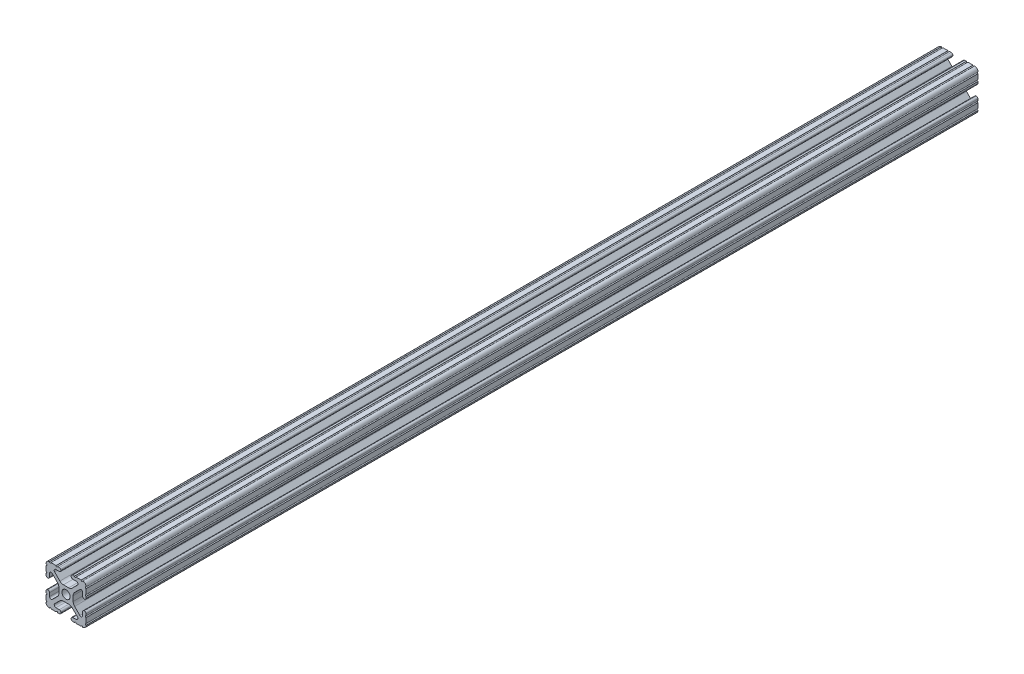
SolidWorks part; units mm, degrees
ref_plane "Front Plane" through (0, 0, 0) normal (0, 0, 1) x (1, 0, 0)
ref_plane "Top Plane" through (0, 0, 0) normal (0, 1, 0) x (1, 0, 0)
ref_plane "Right Plane" through (0, 0, 0) normal (1, 0, 0) x (0, 0, -1)
sketch "Sketch1" plane through (0, 0, 0) normal (0, 0, 1) x (1, 0, 0)
  line L88 (-7.1797, -8.6452) -> (-3.9523, -5.4237)
  line L89 (-1.7093, -4.4958) -> (1.7093, -4.4958)
  line L90 (3.9523, -5.4237) -> (7.1797, -8.6452)
  line L91 (6.4164, -10.4902) -> (4.2875, -10.4902)
  line L92 (3.2385, -11.5392) -> (3.2385, -11.651)
  line L93 (4.2875, -12.7) -> (5.3171, -12.7)
  line L94 (6.3331, -12.7) -> (9.5504, -12.7)
  line L95 (12.7, -9.5504) -> (12.7, -6.3331)
  line L96 (12.7, -5.3171) -> (12.7, -4.2875)
  line L97 (11.651, -3.2385) -> (11.5392, -3.2385)
  line L98 (10.4902, -4.2875) -> (10.4902, -6.4021)
  line L99 (8.7371, -7.1294) -> (5.441, -3.8408)
  line L100 (4.5085, -1.5932) -> (4.5085, 1.5932)
  line L101 (5.441, 3.8408) -> (8.7371, 7.1294)
  line L102 (10.4902, 6.4021) -> (10.4902, 4.2875)
  line L103 (11.5392, 3.2385) -> (11.651, 3.2385)
  line L104 (12.7, 4.2875) -> (12.7, 5.3171)
  line L105 (12.7, 6.3331) -> (12.7, 9.5504)
  line L106 (9.5504, 12.7) -> (6.3331, 12.7)
  line L107 (5.3171, 12.7) -> (4.2875, 12.7)
  line L108 (3.2385, 11.651) -> (3.2385, 11.5392)
  line L109 (4.2875, 10.4902) -> (6.4768, 10.4902)
  line L110 (7.207, 8.7244) -> (3.8983, 5.4232)
  line L111 (1.6558, 4.4958) -> (-1.6558, 4.4958)
  line L112 (-3.8983, 5.4232) -> (-7.207, 8.7244)
  line L113 (-6.4768, 10.4902) -> (-4.2875, 10.4902)
  line L114 (-3.2385, 11.5392) -> (-3.2385, 11.651)
  line L115 (-4.2875, 12.7) -> (-5.3171, 12.7)
  line L116 (-6.3331, 12.7) -> (-9.5504, 12.7)
  line L117 (-12.7, 9.5504) -> (-12.7, 6.3331)
  line L118 (-12.7, 5.3171) -> (-12.7, 4.2875)
  line L119 (-11.651, 3.2385) -> (-11.5392, 3.2385)
  line L120 (-10.4902, 4.2875) -> (-10.4902, 6.4021)
  line L121 (-8.7371, 7.1294) -> (-5.441, 3.8408)
  line L122 (-4.5085, 1.5932) -> (-4.5085, -1.5932)
  line L123 (-5.441, -3.8408) -> (-8.7371, -7.1294)
  line L124 (-10.4902, -6.4021) -> (-10.4902, -4.2875)
  line L125 (-11.5392, -3.2385) -> (-11.651, -3.2385)
  line L126 (-12.7, -4.2875) -> (-12.7, -5.3171)
  line L127 (-12.7, -6.3331) -> (-12.7, -9.5504)
  line L128 (-9.5504, -12.7) -> (-6.3331, -12.7)
  line L129 (-5.3171, -12.7) -> (-4.2875, -12.7)
  line L130 (-3.2385, -11.651) -> (-3.2385, -11.5392)
  line L131 (-4.2875, -10.4902) -> (-6.4164, -10.4902)
  circle A1 centre (0, 0) radius 2.6035
  arc A104 (-7.1797, -8.6452) -> (-6.4164, -10.4902) centre (-6.4164, -9.4098) ccw
  arc A105 (-1.7093, -4.4958) -> (-3.9523, -5.4237) centre (-1.7093, -7.6708) ccw
  arc A106 (3.9523, -5.4237) -> (1.7093, -4.4958) centre (1.7093, -7.6708) ccw
  arc A107 (6.4164, -10.4902) -> (7.1797, -8.6452) centre (6.4164, -9.4098) ccw
  arc A108 (4.2875, -10.4902) -> (3.2385, -11.5392) centre (4.2875, -11.5392) ccw
  arc A109 (3.2385, -11.651) -> (4.2875, -12.7) centre (4.2875, -11.651) ccw
  arc A110 (6.3331, -12.7) -> (5.3171, -12.7) centre (5.8251, -12.7) ccw
  arc A111 (10.5664, -12.6998) -> (9.5504, -12.7) centre (10.0584, -12.7) ccw
  arc A112 (10.5664, -12.6998) -> (12.6998, -10.5664) centre (10.5918, -10.5918) ccw
  arc A113 (12.7, -9.5504) -> (12.6998, -10.5664) centre (12.7, -10.0584) ccw
  arc A114 (12.7, -5.3171) -> (12.7, -6.3331) centre (12.7, -5.8251) ccw
  arc A115 (12.7, -4.2875) -> (11.651, -3.2385) centre (11.651, -4.2875) ccw
  arc A116 (11.5392, -3.2385) -> (10.4902, -4.2875) centre (11.5392, -4.2875) ccw
  arc A117 (8.7371, -7.1294) -> (10.4902, -6.4021) centre (9.4628, -6.4021) ccw
  arc A118 (4.5085, -1.5932) -> (5.441, -3.8408) centre (7.6835, -1.5932) ccw
  arc A119 (5.441, 3.8408) -> (4.5085, 1.5932) centre (7.6835, 1.5932) ccw
  arc A120 (10.4902, 6.4021) -> (8.7371, 7.1294) centre (9.4628, 6.4021) ccw
  arc A121 (10.4902, 4.2875) -> (11.5392, 3.2385) centre (11.5392, 4.2875) ccw
  arc A122 (11.651, 3.2385) -> (12.7, 4.2875) centre (11.651, 4.2875) ccw
  arc A123 (12.7, 6.3331) -> (12.7, 5.3171) centre (12.7, 5.8251) ccw
  arc A124 (12.6998, 10.5664) -> (12.7, 9.5504) centre (12.7, 10.0584) ccw
  arc A125 (12.6998, 10.5664) -> (10.5664, 12.6998) centre (10.5918, 10.5918) ccw
  arc A126 (9.5504, 12.7) -> (10.5664, 12.6998) centre (10.0584, 12.7) ccw
  arc A127 (5.3171, 12.7) -> (6.3331, 12.7) centre (5.8251, 12.7) ccw
  arc A128 (4.2875, 12.7) -> (3.2385, 11.651) centre (4.2875, 11.651) ccw
  arc A129 (3.2385, 11.5392) -> (4.2875, 10.4902) centre (4.2875, 11.5392) ccw
  arc A130 (7.207, 8.7244) -> (6.4768, 10.4902) centre (6.4768, 9.4563) ccw
  arc A131 (1.6558, 4.4958) -> (3.8983, 5.4232) centre (1.6558, 7.6708) ccw
  arc A132 (-3.8983, 5.4232) -> (-1.6558, 4.4958) centre (-1.6558, 7.6708) ccw
  arc A133 (-6.4768, 10.4902) -> (-7.207, 8.7244) centre (-6.4768, 9.4563) ccw
  arc A134 (-4.2875, 10.4902) -> (-3.2385, 11.5392) centre (-4.2875, 11.5392) ccw
  arc A135 (-3.2385, 11.651) -> (-4.2875, 12.7) centre (-4.2875, 11.651) ccw
  arc A136 (-6.3331, 12.7) -> (-5.3171, 12.7) centre (-5.8251, 12.7) ccw
  arc A137 (-10.5664, 12.6998) -> (-9.5504, 12.7) centre (-10.0584, 12.7) ccw
  arc A138 (-10.5664, 12.6998) -> (-12.6998, 10.5664) centre (-10.5918, 10.5918) ccw
  arc A139 (-12.7, 9.5504) -> (-12.6998, 10.5664) centre (-12.7, 10.0584) ccw
  arc A140 (-12.7, 5.3171) -> (-12.7, 6.3331) centre (-12.7, 5.8251) ccw
  arc A141 (-12.7, 4.2875) -> (-11.651, 3.2385) centre (-11.651, 4.2875) ccw
  arc A142 (-11.5392, 3.2385) -> (-10.4902, 4.2875) centre (-11.5392, 4.2875) ccw
  arc A143 (-8.7371, 7.1294) -> (-10.4902, 6.4021) centre (-9.4628, 6.4021) ccw
  arc A144 (-4.5085, 1.5932) -> (-5.441, 3.8408) centre (-7.6835, 1.5932) ccw
  arc A145 (-5.441, -3.8408) -> (-4.5085, -1.5932) centre (-7.6835, -1.5932) ccw
  arc A146 (-10.4902, -6.4021) -> (-8.7371, -7.1294) centre (-9.4628, -6.4021) ccw
  arc A147 (-10.4902, -4.2875) -> (-11.5392, -3.2385) centre (-11.5392, -4.2875) ccw
  arc A148 (-11.651, -3.2385) -> (-12.7, -4.2875) centre (-11.651, -4.2875) ccw
  arc A149 (-12.7, -6.3331) -> (-12.7, -5.3171) centre (-12.7, -5.8251) ccw
  arc A150 (-12.6998, -10.5664) -> (-12.7, -9.5504) centre (-12.7, -10.0584) ccw
  arc A151 (-12.6998, -10.5664) -> (-10.5664, -12.6998) centre (-10.5918, -10.5918) ccw
  arc A152 (-9.5504, -12.7) -> (-10.5664, -12.6998) centre (-10.0584, -12.7) ccw
  arc A153 (-5.3171, -12.7) -> (-6.3331, -12.7) centre (-5.8251, -12.7) ccw
  arc A154 (-4.2875, -12.7) -> (-3.2385, -11.651) centre (-4.2875, -11.651) ccw
  arc A155 (-3.2385, -11.5392) -> (-4.2875, -10.4902) centre (-4.2875, -11.5392) ccw
extrude "Boss-Extrude1" add sketch "Sketch1" along normal mid plane 565.15
